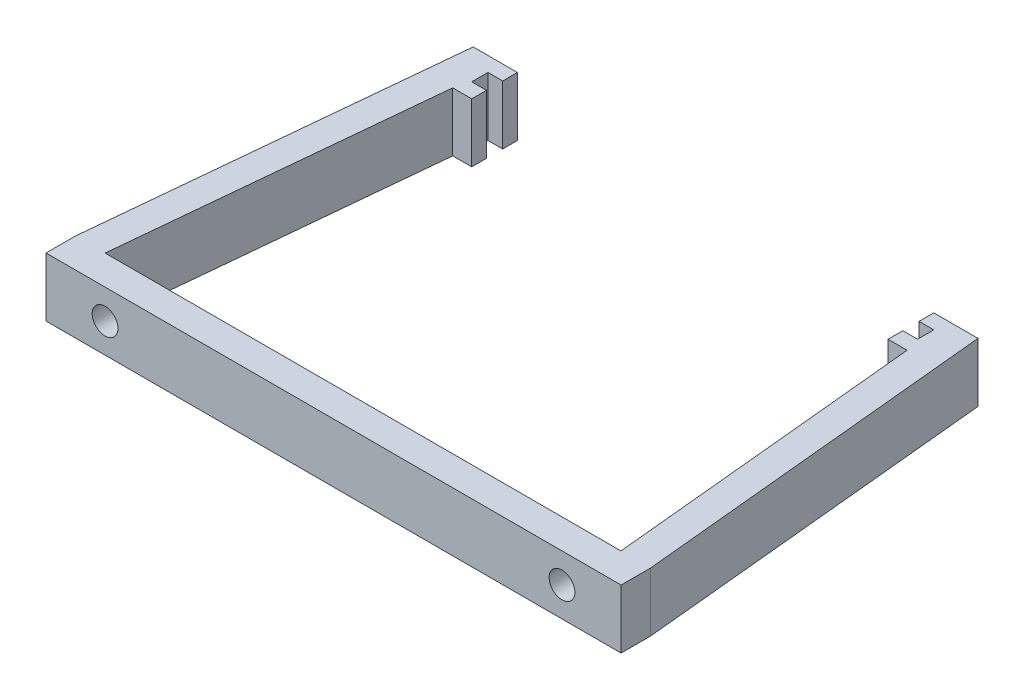
SolidWorks part; units mm, degrees
material "ABS"
ref_plane "Plano frontal" through (0, 0, 0) normal (0, 0, 1) x (1, 0, 0)
ref_plane "Plano superior" through (0, 0, 0) normal (0, 1, 0) x (1, 0, 0)
ref_plane "Plano direito" through (0, 0, 0) normal (1, 0, 0) x (0, 0, -1)
sketch "Esboço1" plane through (0, 0, 0) normal (0, 0, 1) x (1, 0, 0)
  line L0 (-31, 0) -> (31, 0) construction
  line L2 (-35, 4) -> (35, 4)
  line L3 (-35, 4) -> (-35, -4)
  line L4 (-35, -4) -> (35, -4)
  line L5 (35, 4) -> (35, -4)
  line L6 (-35, 4) -> (35, -4) construction
  line L7 (-35, -4) -> (35, 4) construction
  circle A0 centre (-31, 0) radius 1.75
  circle A1 centre (31, 0) radius 1.75
  point P4 (0, 0)
  point P5 (0, 0)
  dimension "D1" = 3.5
  dimension "D2" = 62
  dimension "D3" = 70
  dimension "D4" = 8
extrude "Ressalto-extrusão1" add sketch "Esboço1" along normal blind 4
sketch "Esboço2" plane through (0, 4, 0) normal (0, 1, 0) x (1, 0, 0)
  line L0 (-35, 0) -> (-35, -4)
  line L1 (35, 0) -> (-35, 0) construction
  line L2 (-39.0187, 0) -> (-34.25, 49.2)
  line L3 (-34.25, 49.2) -> (-28.25, 49.2)
  line L4 (-28.25, 49.2) -> (-28.25, 47.2)
  line L5 (-28.25, 47.2) -> (-30.25, 47.2)
  line L6 (-30.25, 47.2) -> (-30.25, 45)
  line L7 (-30.25, 45) -> (-28.25, 45)
  line L8 (-28.25, 45) -> (-28.25, 43)
  line L9 (-28.25, 43) -> (-30.8322, 43)
  line L10 (-30.8322, 43) -> (-35, 0)
  line L11 (0, 29.2585) -> (0, 0) construction
  line L12 (-35, -4) -> (-35, 0) construction
  line L13 (-39.0187, 0) -> (-39.0187, -4)
  line L14 (-39.0187, -4) -> (-35, -4)
  line L15 (39.0187, -4) -> (35, -4)
  line L16 (39.0187, 0) -> (39.0187, -4)
  line L17 (30.8322, 43) -> (35, 0)
  line L18 (28.25, 43) -> (30.8322, 43)
  line L19 (28.25, 45) -> (28.25, 43)
  line L20 (30.25, 45) -> (28.25, 45)
  line L21 (30.25, 47.2) -> (30.25, 45)
  line L22 (28.25, 47.2) -> (30.25, 47.2)
  line L23 (28.25, 49.2) -> (28.25, 47.2)
  line L24 (34.25, 49.2) -> (28.25, 49.2)
  line L25 (39.0187, 0) -> (34.25, 49.2)
  line L26 (35, 0) -> (35, -4)
  point P6 (0, 0)
  dimension "D1" = 2.2
  dimension "D2" = 2
  dimension "D3" = 6
  dimension "D4" = 2
  dimension "D5" = 4
  dimension "D6" = 60.5
  dimension "D7" = 43
extrude "Ressalto-extrusão2" add sketch "Esboço2" against normal up to surface (8 mm away) up to face at (0, -4, 2)
